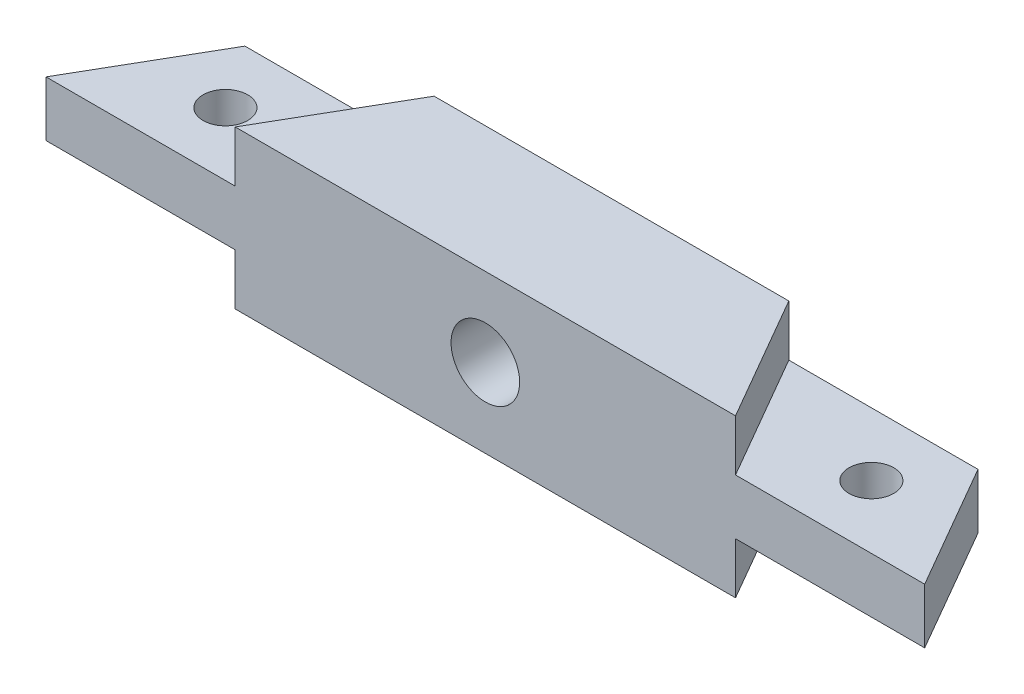
SolidWorks part; units mm, degrees
material "1023 Carbon Steel Sheet (SS)"
ref_plane "Front Plane" through (0, 0, 0) normal (0, 0, 1) x (1, 0, 0)
ref_plane "Top Plane" through (0, 0, 0) normal (0, 1, 0) x (1, 0, 0)
ref_plane "Right Plane" through (0, 0, 0) normal (1, 0, 0) x (0, 0, -1)
sketch "Sketch2" plane through (0, 0, 0) normal (0, 1, 0) x (1, 0, 0)
  line L0 (-17.8594, 6.35) -> (17.8594, 6.35)
  line L1 (17.8594, 6.35) -> (25.1917, -6.35)
  line L2 (25.1917, -6.35) -> (-25.1917, -6.35)
  line L3 (-25.1917, -6.35) -> (-17.8594, 6.35)
  line L4 (0, 6.35) -> (0, -6.35) construction
  point P6 (0, 0)
  dimension "D1" = 35.7188
  dimension "D2" = 12.7
  dimension "D3" = 60
extrude "Boss-Extrude1" add sketch "Sketch2" along normal mid plane 15.875
sketch "Sketch5" plane through (0, 0, 6.35) normal (0, 0, 1) x (1, 0, 0)
  circle A0 centre (0, 0) radius 3.4544
  dimension "D1" = 6.9088
extrude "Cut-Extrude2" cut sketch "Sketch5" against normal through all
sketch "Sketch6" plane through (0, 0, 6.35) normal (0, 0, 1) x (1, 0, 0)
  line L0 (-25.1917, 7.9375) -> (-25.1917, -7.9375) construction
  line L1 (-25.1917, -2.7781) -> (-44.2417, -2.7781)
  line L2 (-25.1917, -2.7781) -> (-25.1917, 2.7781)
  line L3 (-25.1917, 2.7781) -> (-44.2417, 2.7781)
  line L4 (-44.2417, -2.7781) -> (-44.2417, 2.7781)
  line L5 (-25.1917, 7.9375) -> (-25.1917, -7.9375) construction
  point P10 (-25.1917, 0)
  point P11 (-25.1917, 0)
  dimension "D1" = 5.5562
  dimension "D2" = 19.05
sweep "Sweep1" add profiles "Sketch6" path edge at (-21.5255, 7.9375, 0)
sketch "Sketch7" plane through (0, 0, 6.35) normal (0, 0, 1) x (1, 0, 0)
  line L0 (25.1917, 7.9375) -> (25.1917, -7.9375) construction
  line L1 (25.1917, -2.7781) -> (44.2417, -2.7781)
  line L2 (25.1917, -2.7781) -> (25.1917, 2.7781)
  line L3 (25.1917, 2.7781) -> (44.2417, 2.7781)
  line L4 (44.2417, -2.7781) -> (44.2417, 2.7781)
  line L5 (25.1917, -7.9375) -> (25.1917, 7.9375) construction
  point P8 (25.1917, 0)
  point P11 (25.1917, 0)
  dimension "D1" = 19.05
  dimension "D2" = 5.5562
sweep "Sweep2" add profiles "Sketch7" path edge at (21.5255, 7.9375, 0)
sketch "Sketch8" plane through (0, 2.7781, 0) normal (0, 1, 0) x (1, 0, 0)
  line L0 (0, -6.985) -> (0, 6.985) construction
  line L1 (-17.8594, 6.35) -> (-25.1917, -6.35) construction
  circle A0 centre (-32.5241, 0) radius 2.2479
  circle A1 centre (32.5241, 0) radius 2.2479
  dimension "D1" = 4.4958
  dimension "D2" = 9.525
extrude "Cut-Extrude3" cut sketch "Sketch8" against normal up to next
